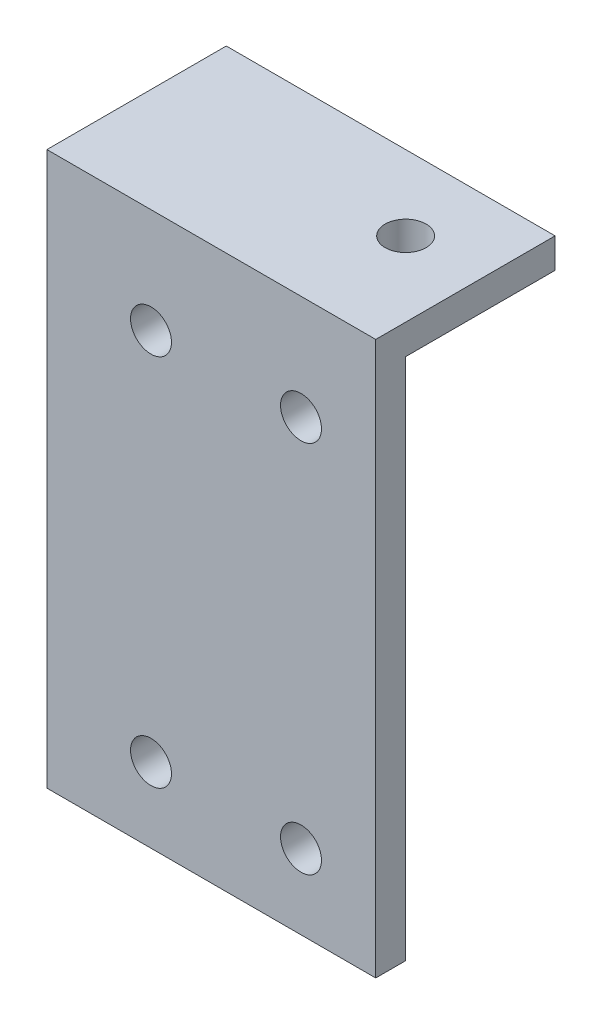
SolidWorks part; units mm, degrees
ref_plane "Front Plane" through (0, 0, 0) normal (0, 0, 1) x (1, 0, 0)
ref_plane "Top Plane" through (0, 0, 0) normal (0, 1, 0) x (1, 0, 0)
ref_plane "Right Plane" through (0, 0, 0) normal (1, 0, 0) x (0, 0, -1)
sketch "Sketch1" plane through (0, 0, 0) normal (0, 0, 1) x (1, 0, 0)
  line L1 (-229.0682, -521.2775) -> (-189.0682, -521.2775)
  line L2 (-229.0682, -521.2775) -> (-229.0682, -451.2775)
  line L3 (-229.0682, -451.2775) -> (-189.0682, -451.2775)
  line L4 (-189.0682, -521.2775) -> (-189.0682, -451.2775)
  line L5 (-229.0682, -521.2775) -> (-189.0682, -451.2775) construction
  line L6 (-229.0682, -451.2775) -> (-189.0682, -521.2775) construction
  circle A0 centre (-199.0682, -461.2775) radius 2.74
  circle A1 centre (-219.1391, -461.2775) radius 2.74
  circle A2 centre (-219.1391, -511.2775) radius 2.74
  circle A3 centre (-199.0682, -511.2775) radius 2.74
  point P0 (-209.0682, -486.2775)
  dimension "D3" = 5.48
  dimension "D6" = 10
  dimension "D1" = 40
  dimension "D2" = 70
  dimension "D4" = 10
  dimension "D5" = 10
extrude "Boss-Extrude1" add sketch "Sketch1" along normal blind 4
sketch "Sketch2" plane through (0, -451.2775, 0) normal (0, 1, 0) x (1, 0, 0)
  line L1 (-229.0682, -4) -> (-189.0682, -4)
  line L2 (-229.0682, -4) -> (-229.0682, 20)
  line L3 (-229.0682, 20) -> (-189.0682, 20)
  line L4 (-189.0682, -4) -> (-189.0682, 20)
  circle A0 centre (-199.0682, 10) radius 2.74
  dimension "D3" = 5.48
  dimension "D4" = 10
  dimension "D5" = 10
  dimension "D1" = 40
  dimension "D2" = 24
extrude "Boss-Extrude2" add sketch "Sketch2" along normal blind 4
sketch "Sketch3" plane through (-229.0682, 0, 0) normal (-1, 0, 0) x (0, 0, 1)
  line L1 (4, -447.2775) -> (-20, -447.2775)
  line L2 (4, -447.2775) -> (4, -521.2775)
  line L3 (4, -521.2775) -> (-20, -521.2775)
  line L4 (-20, -447.2775) -> (-20, -521.2775)
  circle A0 centre (-10, -461.2775) radius 2.74
  circle A1 centre (-10, -511.2775) radius 2.74
  point P9 (-8, -521.2775)
  dimension "D3" = 5.48
  dimension "D4" = 14
  dimension "D5" = 10
  dimension "D6" = 10
  dimension "D1" = 24
  dimension "D2" = 74
extrude "Boss-Extrude3" add sketch "Sketch3" along normal blind 4
